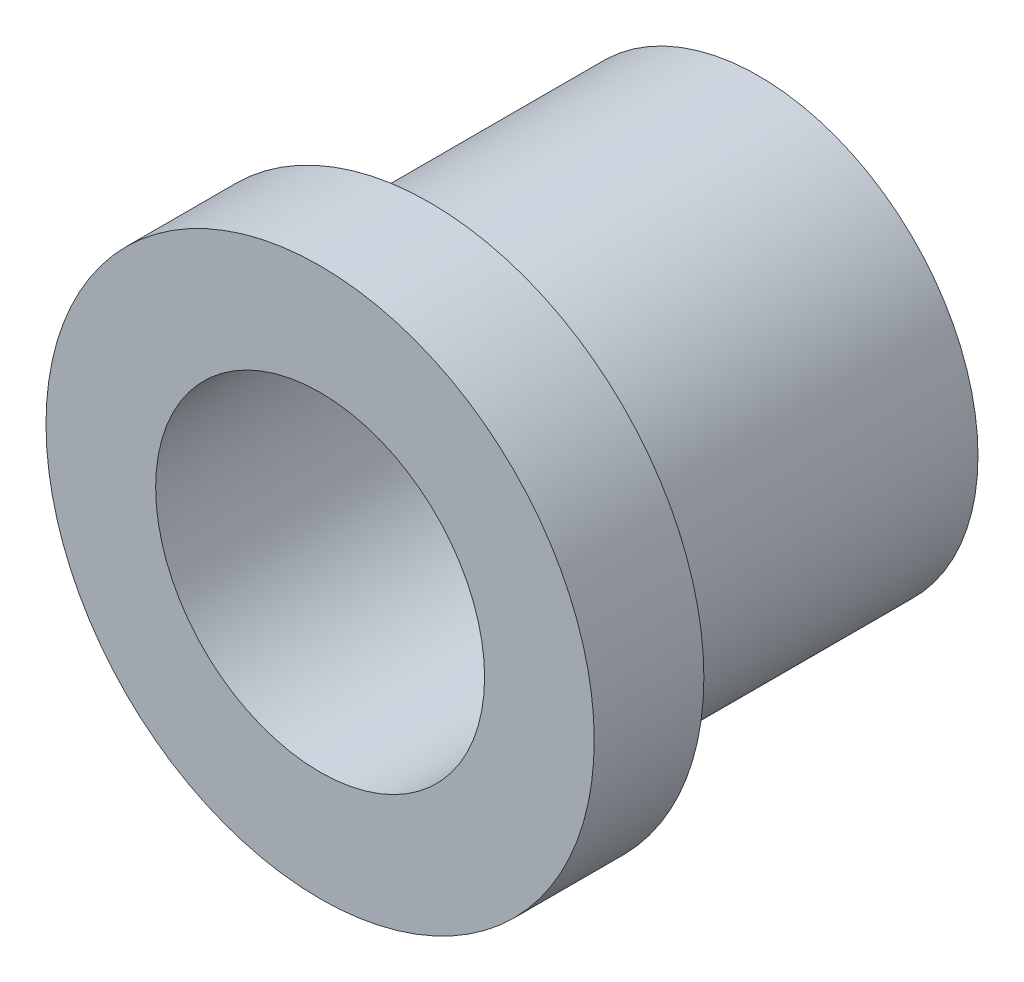
SolidWorks part; units mm, degrees
material "Delrin 2700 NC010, Low Viscosity Acetal Copolymer (SS)"
ref_plane "Front Plane" through (0, 0, 0) normal (0, 0, 1) x (1, 0, 0)
ref_plane "Top Plane" through (0, 0, 0) normal (0, 1, 0) x (1, 0, 0)
ref_plane "Right Plane" through (0, 0, 0) normal (1, 0, 0) x (0, 0, -1)
sketch "Sketch1" plane through (0, 0, 0) normal (1, 0, 0) x (0, 0, -1)
  line L0 (0, 0) -> (10124.8316, 0) construction
  line L1 (0, 7.9375) -> (3.175, 7.9375)
  line L2 (3.175, 7.9375) -> (3.175, 6.35)
  line L3 (3.175, 6.35) -> (12.7, 6.35)
  line L4 (12.7, 6.35) -> (12.7, 4.7625)
  line L5 (12.7, 4.7625) -> (0, 4.7625)
  line L6 (0, 4.7625) -> (0, 7.9375)
  dimension "D1" = 3.175
  dimension "D2" = 4.7625
  dimension "D3" = 1.5875
  dimension "D4" = 1.5875
  dimension "D5" = 12.7
revolve "Revolve1" add sketch "Sketch1" angle 360 about L0
